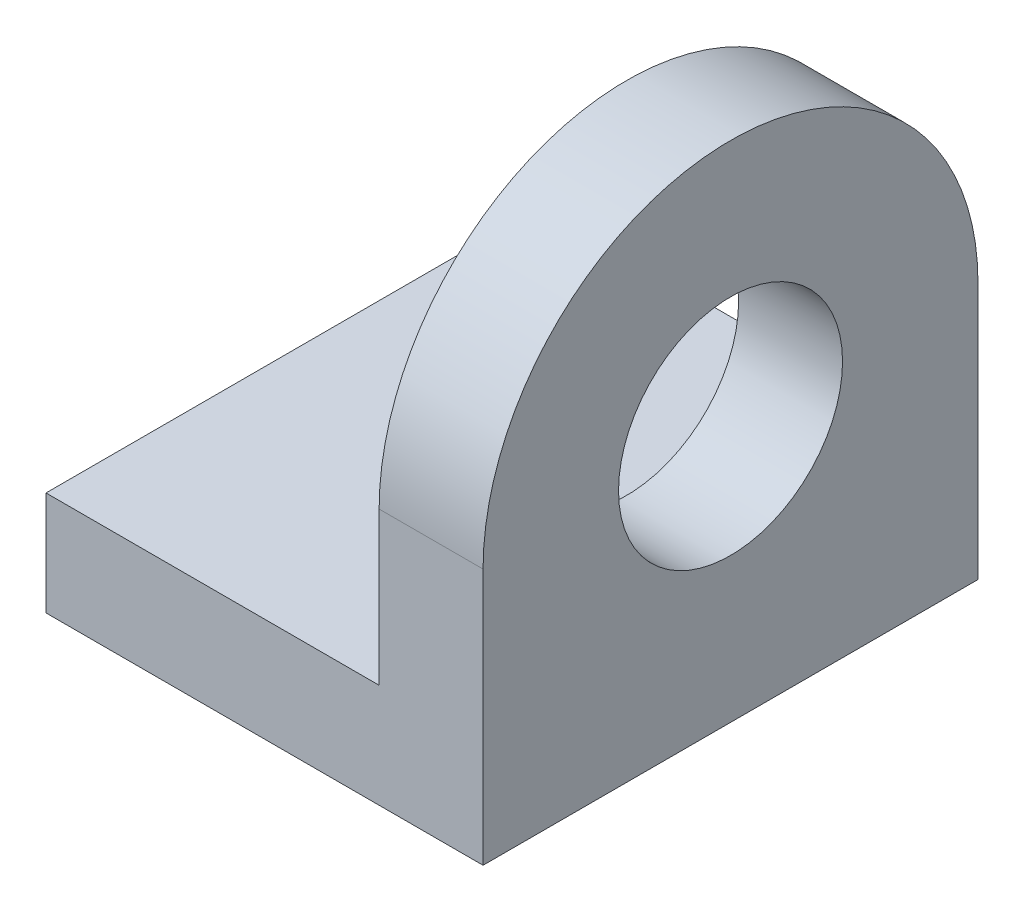
SolidWorks part; units mm, degrees
ref_plane "Front Plane" through (0, 0, 0) normal (0, 0, 1) x (1, 0, 0)
ref_plane "Top Plane" through (0, 0, 0) normal (0, 1, 0) x (1, 0, 0)
ref_plane "Right Plane" through (0, 0, 0) normal (1, 0, 0) x (0, 0, -1)
sketch "Sketch2" plane through (0, 0, 0) normal (0, 1, 0) x (1, 0, 0)
  line L1 (-16.026, 23.8101) -> (0, 23.8101)
  line L2 (-16.026, 23.8101) -> (-16.026, 0)
  line L3 (-16.026, 0) -> (0, 0)
  line L4 (0, 23.8101) -> (0, 0)
extrude "Boss-Extrude1" add sketch "Sketch2" along normal blind 5
sketch "Sketch3" plane through (0, 0, 0) normal (1, 0, 0) x (0, 0, -1)
  line L0 (0, 0) -> (0, 12.3418)
  line L1 (23.8101, 12.3418) -> (23.8101, 0)
  line L2 (23.8101, 0) -> (0, 0)
  arc A0 (0, 12.3418) -> (23.8101, 12.3418) centre (11.9051, 12.3418) cw
  circle A1 centre (11.9051, 12.3418) radius 5.3886
extrude "Boss-Extrude2" add sketch "Sketch3" along normal blind 5
sketch "Sketch4" plane through (0, 0, 0) normal (0, 1, 0) x (1, 0, 0)
  line L0 (-39.6716, 8.9058) -> (-39.6716, 17.5369)
  line L1 (-31.7183, 17.5369) -> (-31.7183, 8.9058)
  line L2 (-31.7183, 8.9058) -> (-39.6716, 8.9058)
  arc A0 (-39.6716, 17.5369) -> (-31.7183, 17.5369) centre (-35.6949, 17.5369) cw
  circle A1 centre (-35.6949, 17.5369) radius 2.1283
